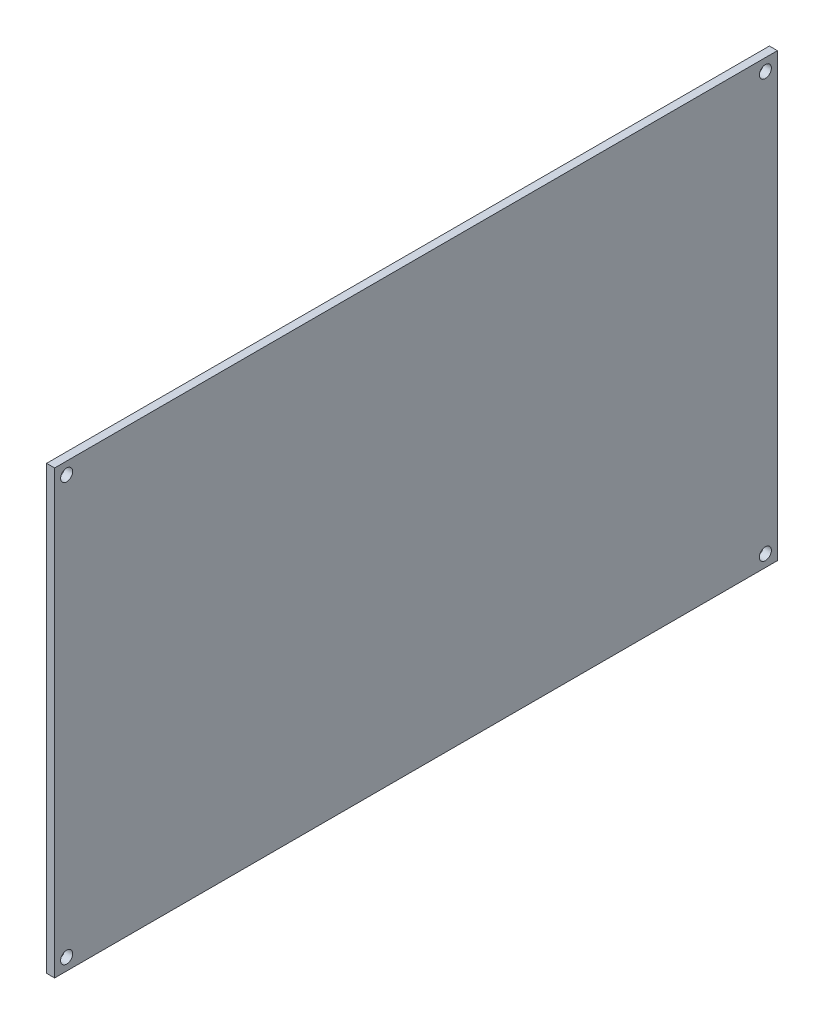
SolidWorks part; units mm, degrees
ref_plane "Front Plane" through (0, 0, 0) normal (0, 0, 1) x (1, 0, 0)
ref_plane "Top Plane" through (0, 0, 0) normal (0, 1, 0) x (1, 0, 0)
ref_plane "Right Plane" through (0, 0, 0) normal (1, 0, 0) x (0, 0, -1)
sketch "Sketch1" plane through (0, 0, 0) normal (1, 0, 0) x (0, 0, -1)
  line L1 (0, 0) -> (180, 0)
  line L2 (0, 0) -> (0, 110)
  line L3 (0, 110) -> (180, 110)
  line L4 (180, 0) -> (180, 110)
  dimension "D1" = 110
  dimension "D2" = 180
extrude "Boss-Extrude1" add sketch "Sketch1" along normal blind 2
sketch "Sketch2" plane through (2, 0, 0) normal (1, 0, 0) x (0, 0, -1)
  line L0 (0, 110) -> (0, 0) construction
  line L1 (0, 0) -> (180, 0) construction
  line L2 (180, 0) -> (180, 110) construction
  line L3 (180, 110) -> (0, 110) construction
  circle A0 centre (3, 107) radius 1.5
  circle A1 centre (177, 107) radius 1.5
  circle A2 centre (177, 3) radius 1.5
  circle A3 centre (3, 3) radius 1.5
  dimension "D1" = 3
  dimension "D2" = 3
  dimension "D3" = 3
  dimension "D4" = 3
  dimension "D5" = 3
  dimension "D6" = 3
  dimension "D7" = 3
  dimension "D8" = 3
  dimension "D9" = 3
  dimension "D10" = 3
  dimension "D11" = 3
  dimension "D12" = 3
extrude "Cut-Extrude1" cut sketch "Sketch2" against normal blind 3
